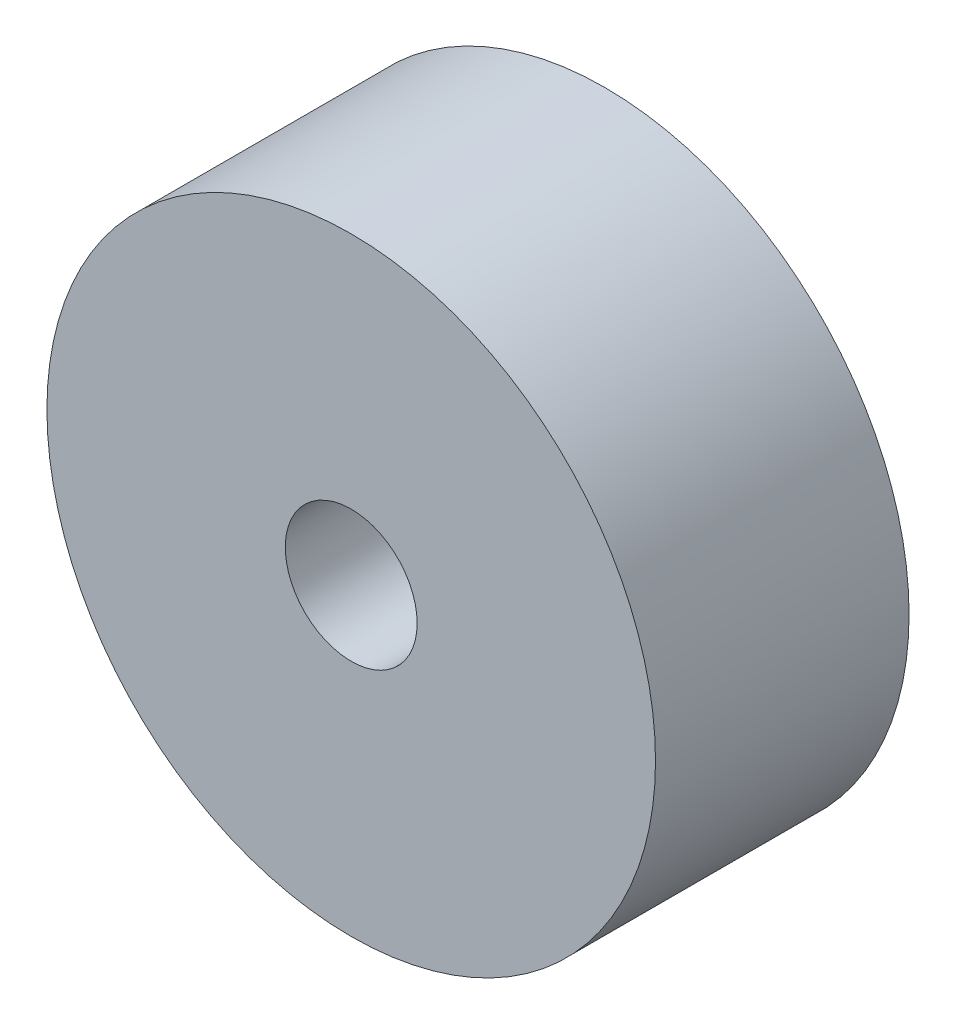
SolidWorks part; units mm, degrees
ref_plane "Front Plane" through (0, 0, 0) normal (0, 0, 1) x (1, 0, 0)
ref_plane "Top Plane" through (0, 0, 0) normal (0, 1, 0) x (1, 0, 0)
ref_plane "Right Plane" through (0, 0, 0) normal (1, 0, 0) x (0, 0, -1)
sketch "Sketch1" plane through (0, 0, 0) normal (0, 0, 1) x (1, 0, 0)
  circle A0 centre (0, 0) radius 6
  circle A1 centre (0, 0) radius 1.3
  dimension "D1" = 12
  dimension "D2" = 2.6
extrude "Boss-Extrude5" add sketch "Sketch1" along normal blind 5
